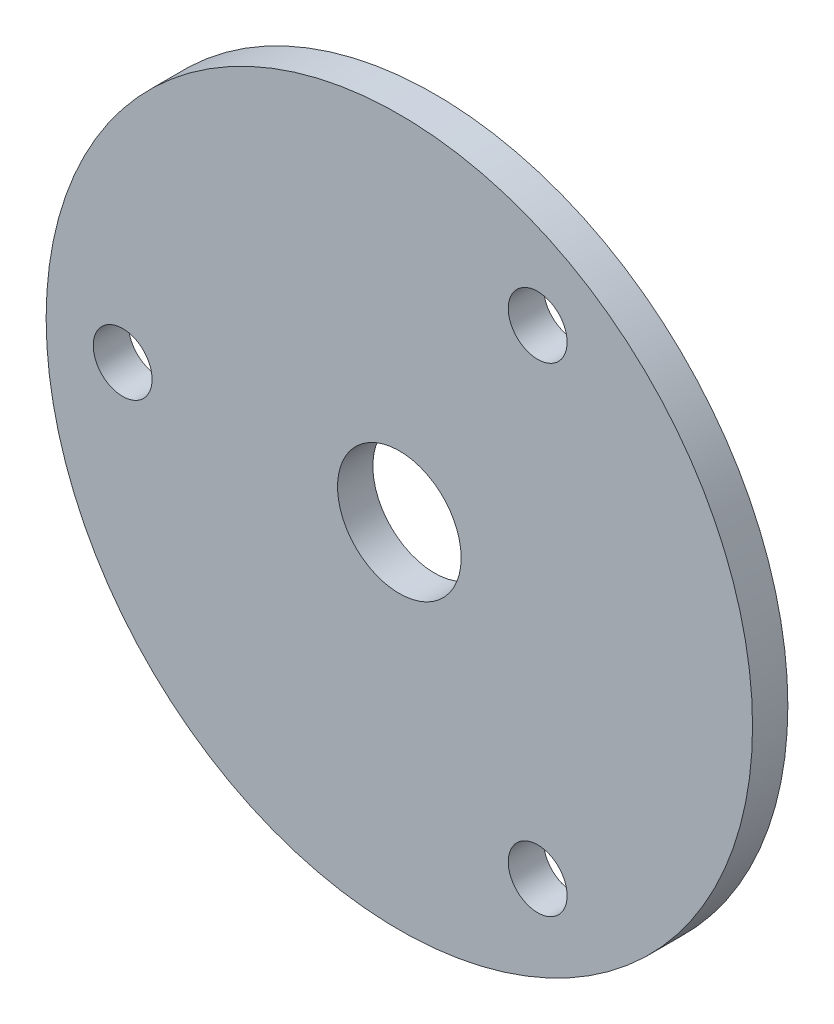
SolidWorks part; units mm, degrees
ref_plane "正面" through (0, 0, 0) normal (0, 0, 1) x (1, 0, 0)
ref_plane "平面" through (0, 0, 0) normal (0, 1, 0) x (1, 0, 0)
ref_plane "右側面" through (0, 0, 0) normal (1, 0, 0) x (0, 0, -1)
sketch "ｽｹｯﾁ1" plane through (0, 0, 0) normal (0, 0, 1) x (1, 0, 0)
  line L0 (-23.5, 0) -> (11.75, -20.3516) construction
  line L1 (11.75, -20.3516) -> (11.75, 20.3516) construction
  line L2 (11.75, 20.3516) -> (-23.5, 0) construction
  circle A0 centre (0, 0) radius 23.5 construction
  circle A2 centre (0, 0) radius 30
  circle A3 centre (-23.5, 0) radius 2.5
  circle A4 centre (11.75, -20.3516) radius 2.5
  circle A5 centre (11.75, 20.3516) radius 2.5
  circle A6 centre (0, 0) radius 5.25
  dimension "D1" = 47
  dimension "D2" = 5
  dimension "D3" = 60
  dimension "D4" = 10.5
extrude "ﾎﾞｽ - 押し出し1" add sketch "ｽｹｯﾁ1" along normal blind 3
